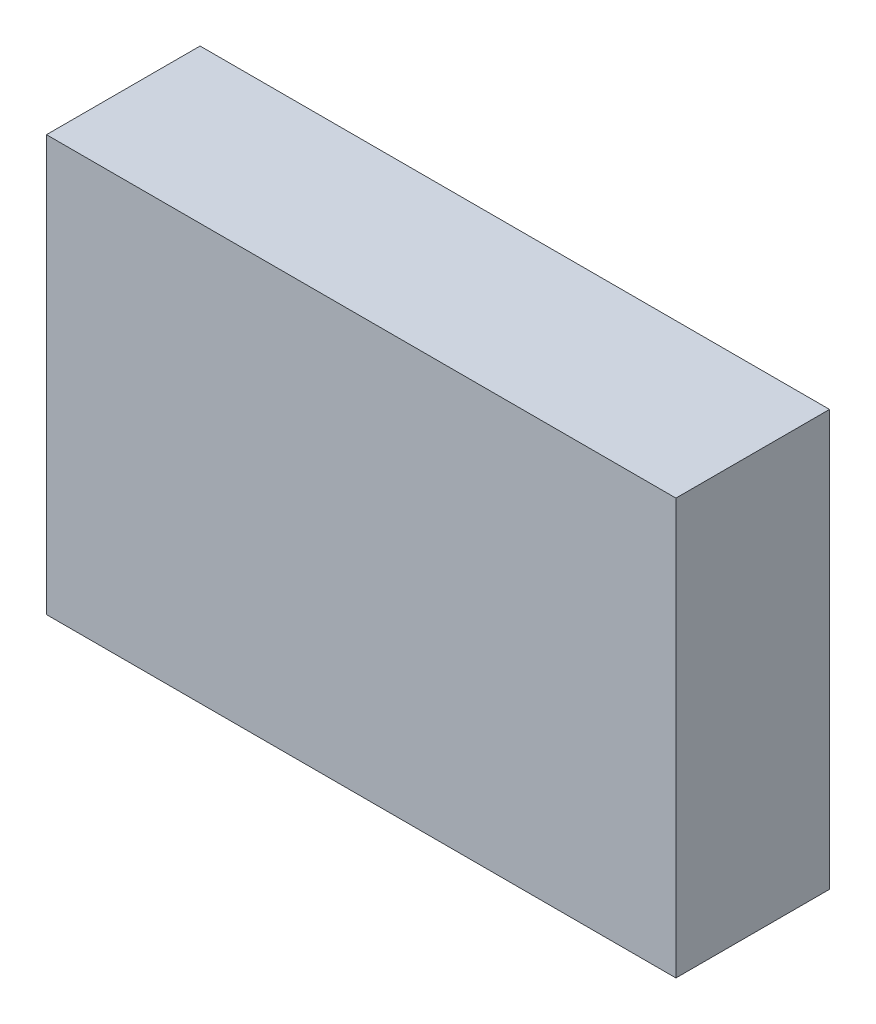
SolidWorks part; units mm, degrees
ref_plane "Спереди" through (0, 0, 0) normal (0, 0, 1) x (1, 0, 0)
ref_plane "Сверху" through (0, 0, 0) normal (0, 1, 0) x (1, 0, 0)
ref_plane "Справа" through (0, 0, 0) normal (1, 0, 0) x (0, 0, -1)
other "Configuration Table"
sketch "Sketch1" plane through (0, 0, 0) normal (0, 0, 1) x (1, 0, 0)
  line L1 (-104.5, -69) -> (104.5, -69)
  line L2 (-104.5, -69) -> (-104.5, 69)
  line L3 (-104.5, 69) -> (104.5, 69)
  line L4 (104.5, -69) -> (104.5, 69)
  line L5 (-104.5, -69) -> (104.5, 69) construction
  line L6 (-104.5, 69) -> (104.5, -69) construction
  point P0 (0, 0)
  dimension "D1" = 209
  dimension "D2" = 138
extrude "Boss-Extrude1" add sketch "Sketch1" along normal mid plane 51
